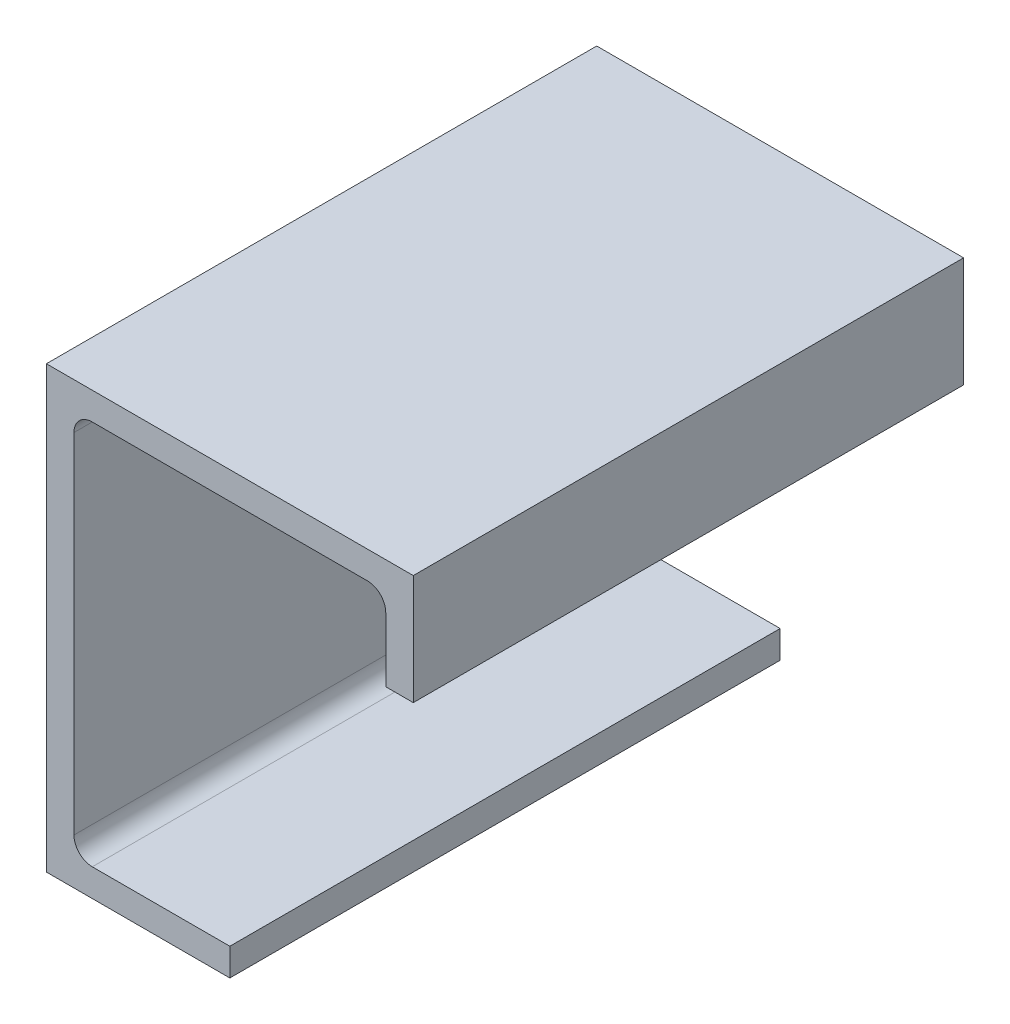
SolidWorks part; units mm, degrees
material "6061 Alloy"
ref_plane "Front Plane" through (0, 0, 0) normal (0, 0, 1) x (1, 0, 0)
ref_plane "Top Plane" through (0, 0, 0) normal (0, 1, 0) x (1, 0, 0)
ref_plane "Right Plane" through (0, 0, 0) normal (1, 0, 0) x (0, 0, -1)
sketch "Sketch2" plane through (0, 0, 0) normal (0, 0, 1) x (1, 0, 0)
  line L0 (0, 0) -> (0, 76.2)
  line L1 (0, 76.2) -> (63.5, 76.2)
  line L2 (63.5, 76.2) -> (63.5, 57.15)
  line L3 (63.5, 57.15) -> (58.7375, 57.15)
  line L4 (58.7375, 57.15) -> (58.7375, 71.4375)
  line L5 (58.7375, 71.4375) -> (4.7625, 71.4375)
  line L6 (4.7625, 71.4375) -> (4.7625, 4.7625)
  line L11 (0, 0) -> (31.75, 0)
  line L12 (31.75, 0) -> (31.75, 4.7625)
  line L13 (31.75, 4.7625) -> (4.7625, 4.7625)
  dimension "D1" = 63.5
  dimension "D2" = 19.05
  dimension "D3" = 76.2
  dimension "D4" = 31.75
  dimension "D5" = 4.7625
  dimension "D6" = 4.7625
  dimension "D7" = 4.7625
  dimension "D8" = 4.7625
extrude "Boss-Extrude1" add sketch "Sketch2" along normal mid plane 95.25
fillet "Fillet1" radius 3.175 1 edges at (4.7625, 71.4375, 0)
fillet "Fillet2" radius 3.175 1 edges at (4.7625, 4.7625, 0)
fillet "Fillet3" radius 3.175 1 edges at (58.7375, 71.4375, 0)
